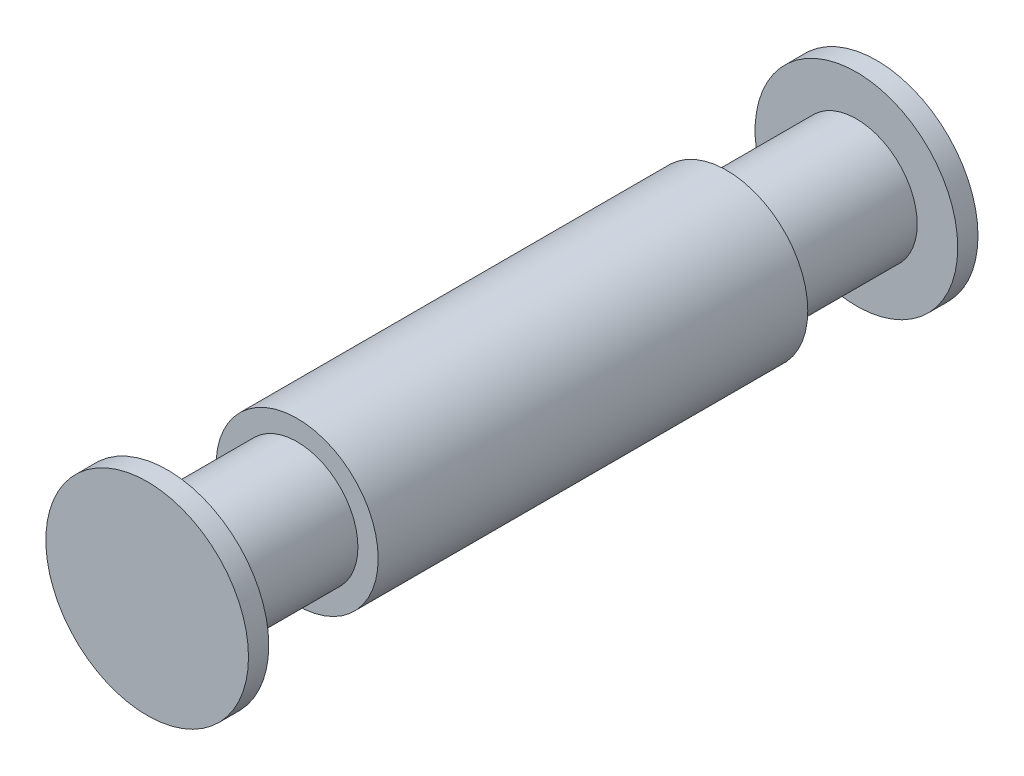
SolidWorks part; units mm, degrees
ref_plane "Front Plane" through (0, 0, 0) normal (0, 0, 1) x (1, 0, 0)
ref_plane "Top Plane" through (0, 0, 0) normal (0, 1, 0) x (1, 0, 0)
ref_plane "Right Plane" through (0, 0, 0) normal (1, 0, 0) x (0, 0, -1)
sketch "Sketch1" plane through (0, 0, 0) normal (1, 0, 0) x (0, 0, -1)
  line L0 (55, 0) -> (-55, 0) construction
  line L1 (-9, 0) -> (9, 0)
  line L2 (-9, 0) -> (-9, 2.5)
  line L4 (9, 0) -> (9, 2.5)
  line L5 (0, 0) -> (0, 1.5) construction
  line L6 (-5.3, 1.5) -> (-5.3, 2)
  line L7 (-5.3, 2) -> (5.3, 2)
  line L8 (5.3, 2) -> (5.3, 1.5)
  line L10 (-9, 2.5) -> (-8.5, 2.5)
  line L11 (-8.5, 2.5) -> (-8.5, 1.5)
  line L12 (-8.5, 1.5) -> (-5.3, 1.5)
  line L13 (5.3, 1.5) -> (8.5, 1.5)
  line L14 (8.5, 1.5) -> (8.5, 2.5)
  line L15 (8.5, 2.5) -> (9, 2.5)
  point P13 (0, 0)
  dimension "D1" = 18
  dimension "D2" = 2.5
  dimension "D3" = 3.7
  dimension "D4" = 2
  dimension "D5" = 2.5
  dimension "D6" = 0.5
  dimension "D7" = 1.5
  dimension "D8" = 0.5
revolve "Revolve1" add sketch "Sketch1" angle 360 about L1
sketch "Sketch2" plane through (0, 0, 5.3) normal (0, 0, 1) x (1, 0, 0)
  line L1 (2, -2) -> (-2, -2)
  line L2 (2, -2) -> (2, 2)
  line L3 (2, 2) -> (-2, 2)
  line L4 (-2, -2) -> (-2, 2)
  line L5 (2, -2) -> (-2, 2) construction
  line L6 (2, 2) -> (-2, -2) construction
  point P0 (0, 0)
  dimension "D1" = 4
extrude "Boss-Extrude1" [suppressed] add sketch "Sketch2" against normal up to surface (10.6 mm away)
